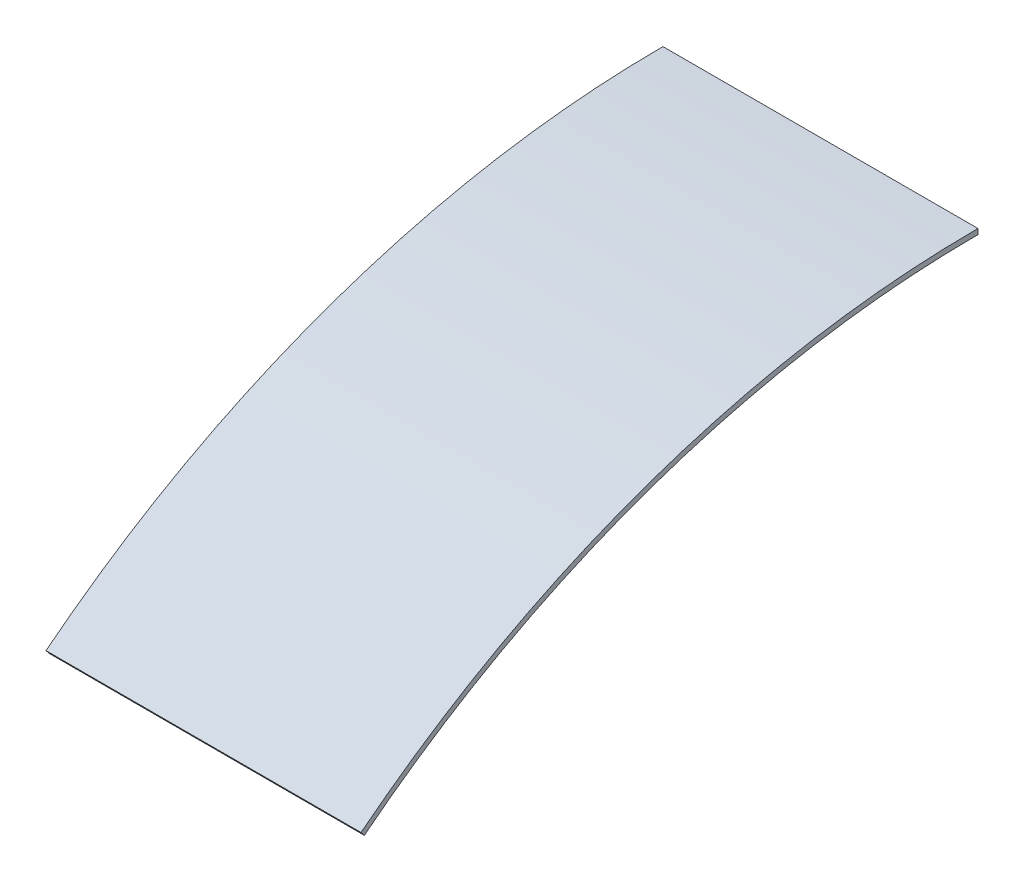
SolidWorks part; units mm, degrees
ref_plane "Front Plane" through (0, 0, 0) normal (0, 0, 1) x (1, 0, 0)
ref_plane "Top Plane" through (0, 0, 0) normal (0, 1, 0) x (1, 0, 0)
ref_plane "Right Plane" through (0, 0, 0) normal (1, 0, 0) x (0, 0, -1)
sketch "Sketch1" plane through (0, 0, 0) normal (1, 0, 0) x (0, 0, -1)
  line L0 (-346.3577, -123.4617) -> (-348.2176, -121.1114)
  line L5 (0, 0) -> (0, -2.9972)
  arc A0 (0, 0) -> (-348.2176, -121.1114) centre (0, -561.1507) ccw
  arc A1 (0, -2.9972) -> (-346.3577, -123.4617) centre (0, -561.1507) ccw
  arc A2 (0, -1.4986) -> (-347.2877, -122.2865) centre (0, -561.1507) ccw
  point P0 (0, -2.9972)
  point P1 (0, 0)
  point P2 (-88.0378, -38.0531)
  point P5 (0, 0)
  point P8 (46.2464, -18.1134)
  point P13 (-95.1206, -34.792)
  point P14 (-9.5644, -8.5045)
  point P15 (0.2802, -1.4722)
  point P16 (-68.103, -16.1521)
  point P17 (0, 0)
  point P18 (0, 0)
  dimension "D3" = 559.6521
  dimension "D1" = 2.9972
  dimension "D2" = 374.65
extrude "Boss-Extrude1" add sketch "Sketch1" along normal blind 177.8 contours L5 A2 L0 A1 | A2 L5 A0 L0
equation "\"WallThickness\"=0.118"
equation "\"D1\"= \"WallThickness\""
equation "\"D1@Sketch1\"=\"WallThickness\""
